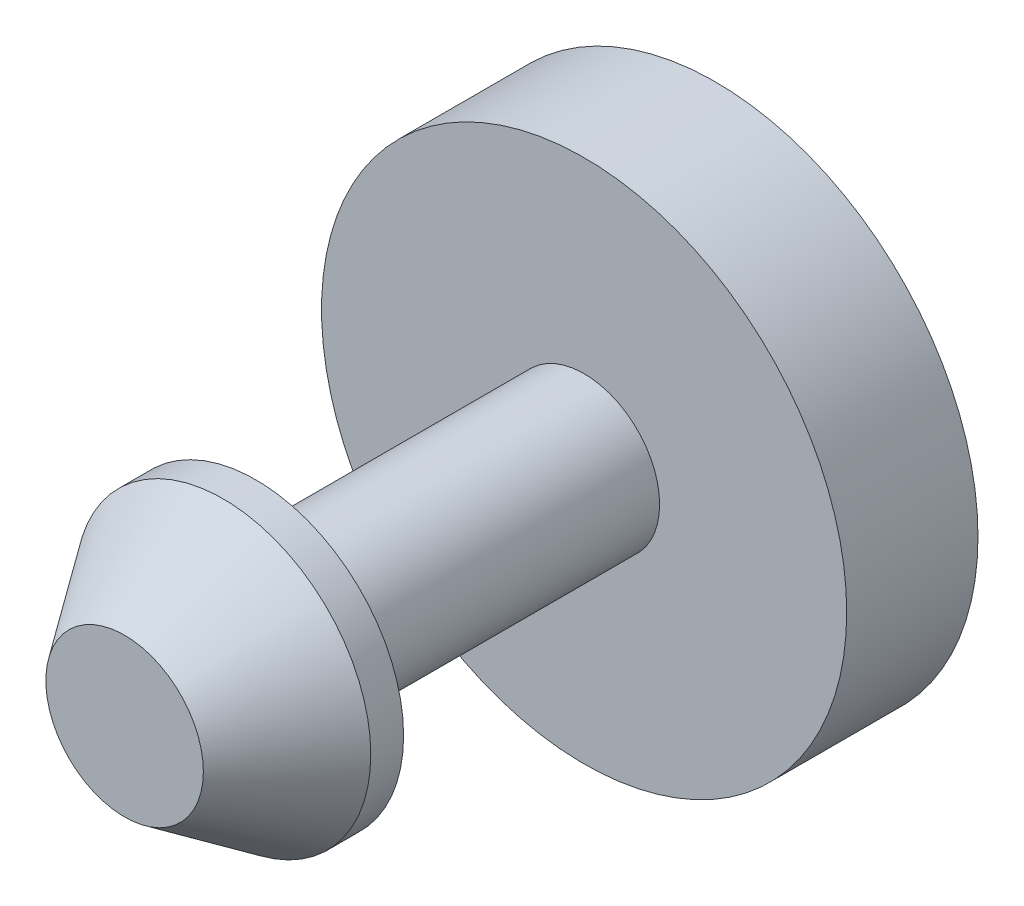
SolidWorks part; units mm, degrees
ref_plane "정면" through (0, 0, 0) normal (0, 0, 1) x (1, 0, 0)
ref_plane "윗면" through (0, 0, 0) normal (0, 1, 0) x (1, 0, 0)
ref_plane "우측면" through (0, 0, 0) normal (1, 0, 0) x (0, 0, -1)
sketch "스케치1" plane through (0, 0, 0) normal (0, 0, 1) x (1, 0, 0)
  circle A0 centre (0, 0) radius 4
  dimension "D1" = 8
extrude "보스-돌출1" add sketch "스케치1" along normal blind 2
sketch "스케치2" plane through (0, 0, 2) normal (0, 0, 1) x (1, 0, 0)
  circle A0 centre (0, 0) radius 1.15
  dimension "D1" = 2.3
extrude "보스-돌출2" add sketch "스케치2" along normal blind 5
sketch "스케치3" plane through (0, 0, 7) normal (0, 0, 1) x (1, 0, 0)
  circle A0 centre (0, 0) radius 2.25
  dimension "D1" = 4.5
extrude "보스-돌출3" add sketch "스케치3" along normal blind 0.5
sketch "스케치4" plane through (0, 0, 7.5) normal (0, 0, 1) x (1, 0, 0)
  circle A0 centre (0, 0) radius 2.25
extrude "보스-돌출4" add sketch "스케치4" along normal blind 1.5 draft 35
